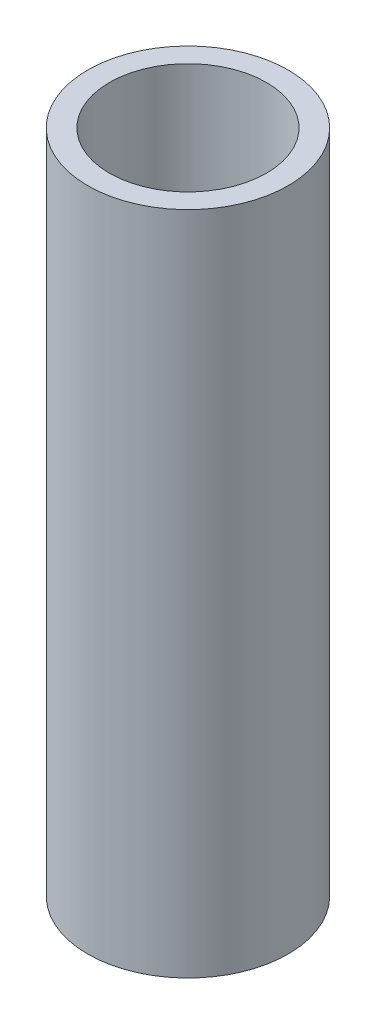
SolidWorks part; units mm, degrees
ref_plane "Front Plane" through (0, 0, 0) normal (0, 0, 1) x (1, 0, 0)
ref_plane "Top Plane" through (0, 0, 0) normal (0, 1, 0) x (1, 0, 0)
ref_plane "Right Plane" through (0, 0, 0) normal (1, 0, 0) x (0, 0, -1)
sketch "Sketch1" plane through (0, 0, 0) normal (0, 1, 0) x (1, 0, 0)
  circle A0 centre (0, 0) radius 6.25
extrude "Boss-Extrude1" add sketch "Sketch1" along normal blind 41.5
sketch "Sketch2" plane through (0, 41.5, 0) normal (0, 1, 0) x (1, 0, 0)
  circle A0 centre (0, 0) radius 4.9
extrude "Cut-Extrude1" cut sketch "Sketch2" against normal through all
